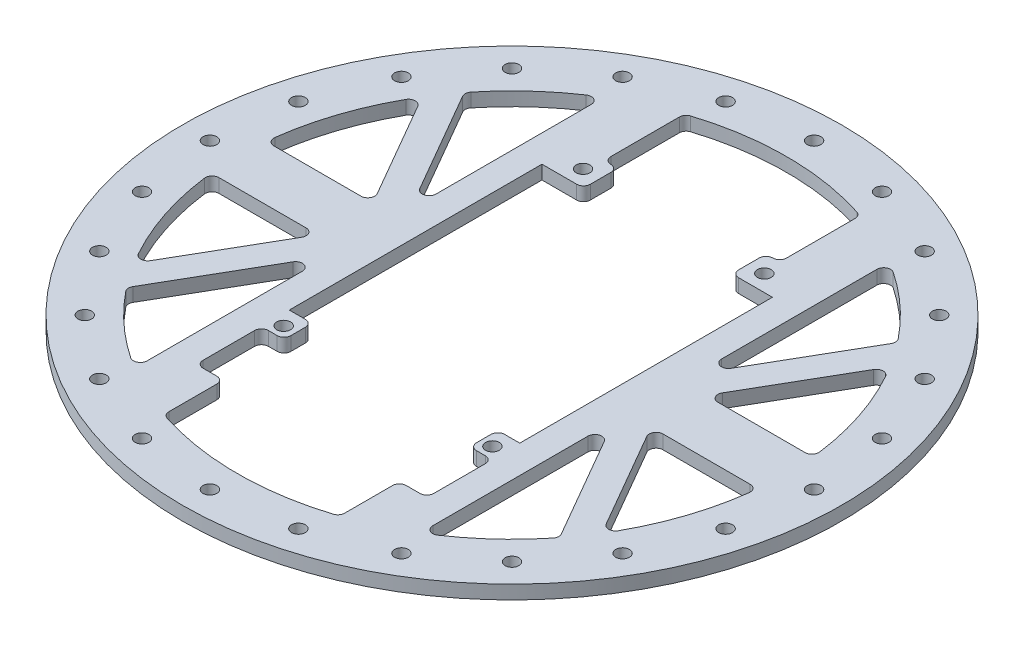
SolidWorks part; units mm, degrees
material "Teak"
ref_plane "Front Plane" through (0, 0, 0) normal (0, 0, 1) x (1, 0, 0)
ref_plane "Top Plane" through (0, 0, 0) normal (0, 1, 0) x (1, 0, 0)
ref_plane "Right Plane" through (0, 0, 0) normal (1, 0, 0) x (0, 0, -1)
sketch "Sketch1" plane through (0, 0, 0) normal (0, 1, 0) x (1, 0, 0)
  line L0 (-52.7093, 30.9279) -> (-39.8941, 8.7312)
  line L1 (-41.2689, 6.35) -> (-61.4016, 6.35)
  line L2 (-33.02, -15.4496) -> (-33.02, -51.3369)
  line L3 (-49.5294, -38.1202) -> (-35.9823, -14.6559)
  line L4 (33.02, -51.3369) -> (33.02, -15.4496)
  line L5 (35.9823, -14.6559) -> (49.5294, -38.1202)
  line L6 (49.5294, 38.1202) -> (35.9823, 14.6559)
  line L7 (33.02, 15.4496) -> (33.02, 51.3369)
  line L8 (18.7308, 33.6778) -> (26.5374, 33.6778)
  line L9 (26.5374, 33.6778) -> (26.5374, -24.7422)
  line L10 (26.5374, -24.7422) -> (23.0425, -24.7422)
  line L11 (21.455, -26.3297) -> (21.455, -29.6672)
  line L12 (23.0425, -31.2547) -> (25.0825, -31.2547)
  line L13 (26.67, -32.8422) -> (26.67, -44.7675)
  line L14 (25.0825, -46.355) -> (21.9075, -46.355)
  line L15 (20.32, -47.9425) -> (20.32, -59.0106)
  line L16 (-20.32, -59.0106) -> (-20.32, -47.9425)
  line L17 (-21.9075, -46.355) -> (-25.0825, -46.355)
  line L18 (-26.67, -44.7675) -> (-26.67, -32.8422)
  line L19 (-25.0825, -31.2547) -> (-23.0425, -31.2547)
  line L20 (-21.455, -29.6672) -> (-21.455, -26.3297)
  line L21 (-23.0425, -24.7422) -> (-26.7518, -24.7422)
  line L22 (-26.7518, -24.7422) -> (-26.7518, 33.6778)
  line L23 (-26.7518, 33.6778) -> (-18.7325, 33.6778)
  line L24 (-17.145, 35.2653) -> (-17.145, 39.9977)
  line L25 (-20.32, 43.1727) -> (-20.32, 59.0106)
  line L26 (20.32, 59.0106) -> (20.32, 43.1727)
  line L27 (17.145, 39.9977) -> (17.1433, 35.2712)
  line L28 (52.7093, -30.9279) -> (39.8941, -8.7313)
  line L29 (41.2689, -6.35) -> (61.4016, -6.35)
  line L30 (-33.02, 51.3369) -> (-33.02, 15.4496)
  line L31 (-35.9823, 14.6559) -> (-49.5294, 38.1202)
  line L32 (61.4016, 6.35) -> (41.2689, 6.35)
  line L33 (39.8941, 8.7312) -> (52.7093, 30.9279)
  line L34 (-61.4016, -6.35) -> (-41.2689, -6.35)
  line L35 (-39.8941, -8.7312) -> (-52.7093, -30.9279)
  arc A0 (-52.7093, 30.9279) -> (-55.4709, 30.9068) centre (-54.0841, 30.1341) ccw
  arc A1 (-41.2689, 6.35) -> (-39.8941, 8.7312) centre (-41.2689, 7.9375) ccw
  arc A2 (-62.976, 8.141) -> (-61.4016, 6.35) centre (-61.4016, 7.9375) ccw
  arc A3 (-55.4709, 30.9068) -> (-62.976, 8.141) centre (0, 0) ccw
  arc A4 (-33.02, -15.4496) -> (-35.9823, -14.6559) centre (-34.6075, -15.4496) ccw
  arc A5 (-35.4949, -52.6532) -> (-33.02, -51.3369) centre (-34.6075, -51.3369) ccw
  arc A6 (-49.3893, -39.9117) -> (-35.4949, -52.6532) centre (0, 0) ccw
  arc A7 (-49.5294, -38.1202) -> (-49.3893, -39.9117) centre (-48.1546, -38.9139) ccw
  arc A8 (49.3893, -39.9117) -> (49.5294, -38.1202) centre (48.1546, -38.9139) ccw
  arc A9 (35.4949, -52.6532) -> (49.3893, -39.9117) centre (0, 0) ccw
  arc A10 (33.02, -51.3369) -> (35.4949, -52.6532) centre (34.6075, -51.3369) ccw
  arc A11 (35.9823, -14.6559) -> (33.02, -15.4496) centre (34.6075, -15.4496) ccw
  arc A12 (35.4949, 52.6532) -> (33.02, 51.3369) centre (34.6075, 51.3369) ccw
  arc A13 (49.3893, 39.9117) -> (35.4949, 52.6532) centre (0, 0) ccw
  arc A14 (49.5294, 38.1202) -> (49.3893, 39.9117) centre (48.1546, 38.9139) ccw
  arc A15 (33.02, 15.4496) -> (35.9823, 14.6559) centre (34.6075, 15.4496) ccw
  arc A16 (17.1433, 35.2712) -> (18.7308, 33.6778) centre (18.7308, 35.2653) ccw
  arc A17 (23.0425, -24.7422) -> (21.455, -26.3297) centre (23.0425, -26.3297) ccw
  arc A18 (21.455, -29.6672) -> (23.0425, -31.2547) centre (23.0425, -29.6672) ccw
  arc A19 (26.67, -32.8422) -> (25.0825, -31.2547) centre (25.0825, -32.8422) ccw
  arc A20 (25.0825, -46.355) -> (26.67, -44.7675) centre (25.0825, -44.7675) ccw
  arc A21 (21.9075, -46.355) -> (20.32, -47.9425) centre (21.9075, -47.9425) ccw
  arc A22 (19.2128, -60.5237) -> (20.32, -59.0106) centre (18.7325, -59.0106) ccw
  arc A23 (-19.2128, -60.5237) -> (19.2128, -60.5237) centre (0, 0) ccw
  arc A24 (-20.32, -59.0106) -> (-19.2128, -60.5237) centre (-18.7325, -59.0106) ccw
  arc A25 (-20.32, -47.9425) -> (-21.9075, -46.355) centre (-21.9075, -47.9425) ccw
  arc A26 (-26.67, -44.7675) -> (-25.0825, -46.355) centre (-25.0825, -44.7675) ccw
  arc A27 (-25.0825, -31.2547) -> (-26.67, -32.8422) centre (-25.0825, -32.8422) ccw
  arc A28 (-23.0425, -31.2547) -> (-21.455, -29.6672) centre (-23.0425, -29.6672) ccw
  arc A29 (-21.455, -26.3297) -> (-23.0425, -24.7422) centre (-23.0425, -26.3297) ccw
  arc A30 (-18.7325, 33.6778) -> (-17.145, 35.2653) centre (-18.7325, 35.2653) ccw
  arc A31 (-17.145, 39.9977) -> (-18.7325, 41.5852) centre (-18.7325, 39.9977) ccw
  arc A32 (-20.32, 43.1727) -> (-18.7325, 41.5852) centre (-18.7325, 43.1727) ccw
  arc A33 (-19.2128, 60.5237) -> (-20.32, 59.0106) centre (-18.7325, 59.0106) ccw
  arc A34 (19.2128, 60.5237) -> (-19.2128, 60.5237) centre (0, 0) ccw
  arc A35 (20.32, 59.0106) -> (19.2128, 60.5237) centre (18.7325, 59.0106) ccw
  arc A36 (18.7325, 41.5852) -> (20.32, 43.1727) centre (18.7325, 43.1727) ccw
  arc A37 (18.7325, 41.5852) -> (17.145, 39.9977) centre (18.7325, 39.9977) ccw
  arc A38 (52.7093, -30.9279) -> (55.4709, -30.9068) centre (54.0841, -30.1341) ccw
  arc A39 (41.2689, -6.35) -> (39.8941, -8.7313) centre (41.2689, -7.9375) ccw
  arc A40 (62.976, -8.141) -> (61.4016, -6.35) centre (61.4016, -7.9375) ccw
  arc A41 (55.4709, -30.9068) -> (62.976, -8.141) centre (0, 0) ccw
  arc A42 (-33.02, 51.3369) -> (-35.4949, 52.6532) centre (-34.6075, 51.3369) ccw
  arc A43 (-35.9823, 14.6559) -> (-33.02, 15.4496) centre (-34.6075, 15.4496) ccw
  arc A44 (-49.3893, 39.9117) -> (-49.5294, 38.1202) centre (-48.1546, 38.9139) ccw
  arc A45 (-35.4949, 52.6532) -> (-49.3893, 39.9117) centre (0, 0) ccw
  arc A46 (55.4709, 30.9068) -> (52.7093, 30.9279) centre (54.0841, 30.1341) ccw
  arc A47 (62.976, 8.141) -> (55.4709, 30.9068) centre (0, 0) ccw
  arc A48 (61.4016, 6.35) -> (62.976, 8.141) centre (61.4016, 7.9375) ccw
  arc A49 (39.8941, 8.7312) -> (41.2689, 6.35) centre (41.2689, 7.9375) ccw
  arc A50 (-55.4709, -30.9068) -> (-52.7093, -30.9279) centre (-54.0841, -30.1341) ccw
  arc A51 (-62.976, -8.141) -> (-55.4709, -30.9068) centre (0, 0) ccw
  arc A52 (-61.4016, -6.35) -> (-62.976, -8.141) centre (-61.4016, -7.9375) ccw
  arc A53 (-39.8941, -8.7312) -> (-41.2689, -6.35) centre (-41.2689, -7.9375) ccw
  circle A54 centre (-34.925, 60.4919) radius 1.5875
  circle A55 centre (20.8477, 37.4877) radius 1.5875
  circle A56 centre (-18.0785, -67.4699) radius 1.5875
  circle A57 centre (-49.3914, -49.3914) radius 1.5875
  circle A58 centre (-67.4699, -18.0785) radius 1.5875
  circle A59 centre (-67.4699, 18.0785) radius 1.5875
  circle A60 centre (-49.3914, 49.3914) radius 1.5875
  circle A61 centre (-18.0785, 67.4699) radius 1.5875
  circle A62 centre (18.0785, 67.4699) radius 1.5875
  circle A63 centre (49.3914, 49.3914) radius 1.5875
  circle A64 centre (67.4699, 18.0785) radius 1.5875
  circle A65 centre (67.4699, -18.0785) radius 1.5875
  circle A66 centre (49.3914, -49.3914) radius 1.5875
  circle A67 centre (18.0785, -67.4699) radius 1.5875
  circle A68 centre (0, -69.85) radius 1.5875
  circle A69 centre (-24.2373, -28.5523) radius 1.5875
  circle A70 centre (34.925, -60.4919) radius 1.5875
  circle A71 centre (60.4919, -34.925) radius 1.5875
  circle A72 centre (69.85, 0) radius 1.5875
  circle A73 centre (60.4919, 34.925) radius 1.5875
  circle A74 centre (34.925, 60.4919) radius 1.5875
  circle A75 centre (0, 69.85) radius 1.5875
  circle A76 centre (-60.4919, 34.925) radius 1.5875
  circle A77 centre (-69.85, 0) radius 1.5875
  circle A78 centre (-60.4919, -34.925) radius 1.5875
  circle A79 centre (-34.925, -60.4919) radius 1.5875
  circle A80 centre (24.0227, -28.5523) radius 1.5875
  circle A81 centre (-21.0623, 37.4877) radius 1.5875
  circle A82 centre (0, 0) radius 76.2
extrude "Boss-Extrude1" add sketch "Sketch1" along normal blind 3.175
